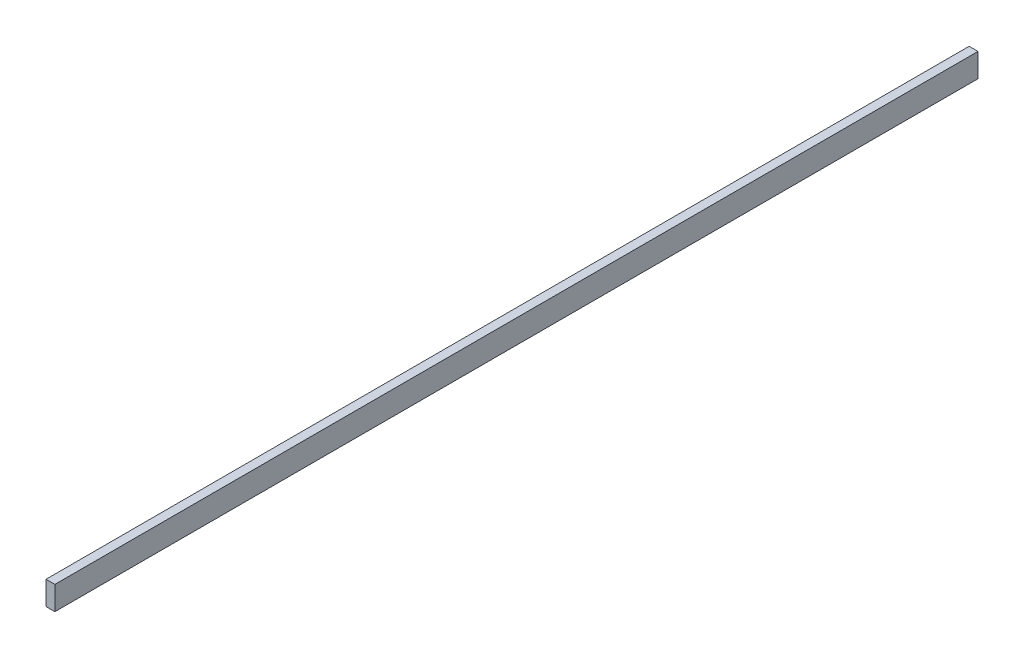
SolidWorks part; units mm, degrees
material "Balsa"
ref_plane "Front Plane" through (0, 0, 0) normal (1, 0, 0) x (0, 1, 0)
ref_plane "Top Plane" through (0, 0, 0) normal (0, 0, 1) x (0, 1, 0)
ref_plane "Right Plane" through (0, 0, 0) normal (0, 1, 0) x (-1, 0, 0)
sketch "Sketch1" plane through (0, 0, 0) normal (1, 0, 0) x (0, 1, 0)
  line L1 (-4, -156) -> (4, -156)
  line L2 (-4, -156) -> (-4, 156)
  line L3 (-4, 156) -> (4, 156)
  line L4 (4, -156) -> (4, 156)
  line L5 (-4, -156) -> (4, 156) construction
  line L6 (-4, 156) -> (4, -156) construction
  point P0 (0, 0)
  dimension "D1" = 8
  dimension "D2" = 312
extrude "Boss-Extrude1" add sketch "Sketch1" along normal mid plane 3
